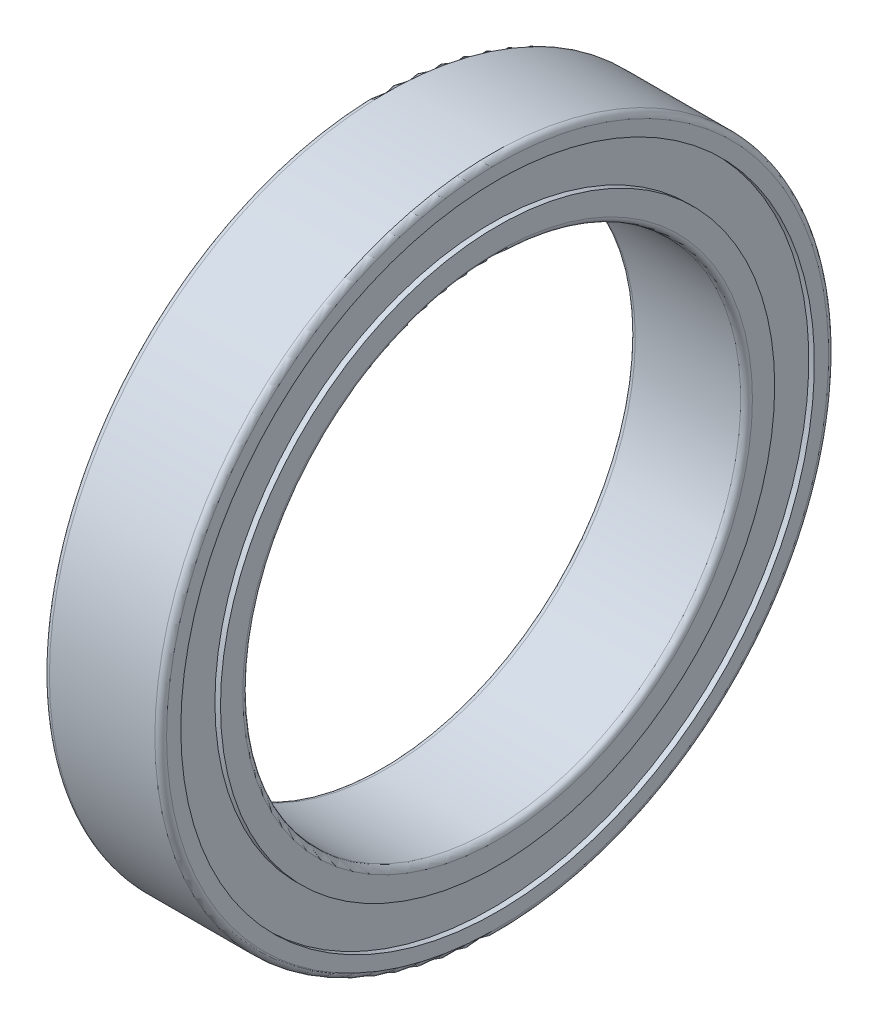
SolidWorks part; units mm, degrees
ref_plane "Front Plane" through (0, 0, 0) normal (0, 0, 1) x (1, 0, 0)
ref_plane "Top Plane" through (0, 0, 0) normal (0, 1, 0) x (1, 0, 0)
ref_plane "Right Plane" through (0, 0, 0) normal (1, 0, 0) x (0, 0, -1)
sketch "Sketch1" plane through (0, 0, 0) normal (0, 0, 1) x (1, 0, 0)
  line L0 (0, 0) -> (4, 0) construction
  line L1 (0, 8.5) -> (4, 8.5)
  line L2 (0, 11.5) -> (4, 11.5)
  line L3 (0, 11.5) -> (0, 10.815)
  line L4 (0, 10.815) -> (0.19, 10.815)
  line L5 (4, 11.5) -> (4, 10.815)
  line L6 (0.19, 10.815) -> (0.19, 9.46)
  line L7 (0.19, 9.46) -> (0, 9.46)
  line L8 (0, 9.46) -> (0, 8.5)
  line L9 (4, 10.815) -> (3.81, 10.815)
  line L10 (3.81, 10.815) -> (3.81, 9.46)
  line L11 (3.81, 9.46) -> (4, 9.46)
  line L12 (4, 9.46) -> (4, 8.5)
  dimension "D" = 23
  dimension "B" = 4
  dimension "D_s" = 17
  dimension "MSM_1" = 21.63
  dimension "MSM_2" = 18.92
  dimension "MSM_3" = 0.19
revolve "Revolve1" add sketch "Sketch1" angle 360 about L0
fillet "Fillet1" radius 0.2 2 edges at (4, 0, 11.5) (0, 0, 11.5)
fillet "Fillet2" radius 0.2 2 edges at (4, 0, 8.5) (0, 0, 8.5)
